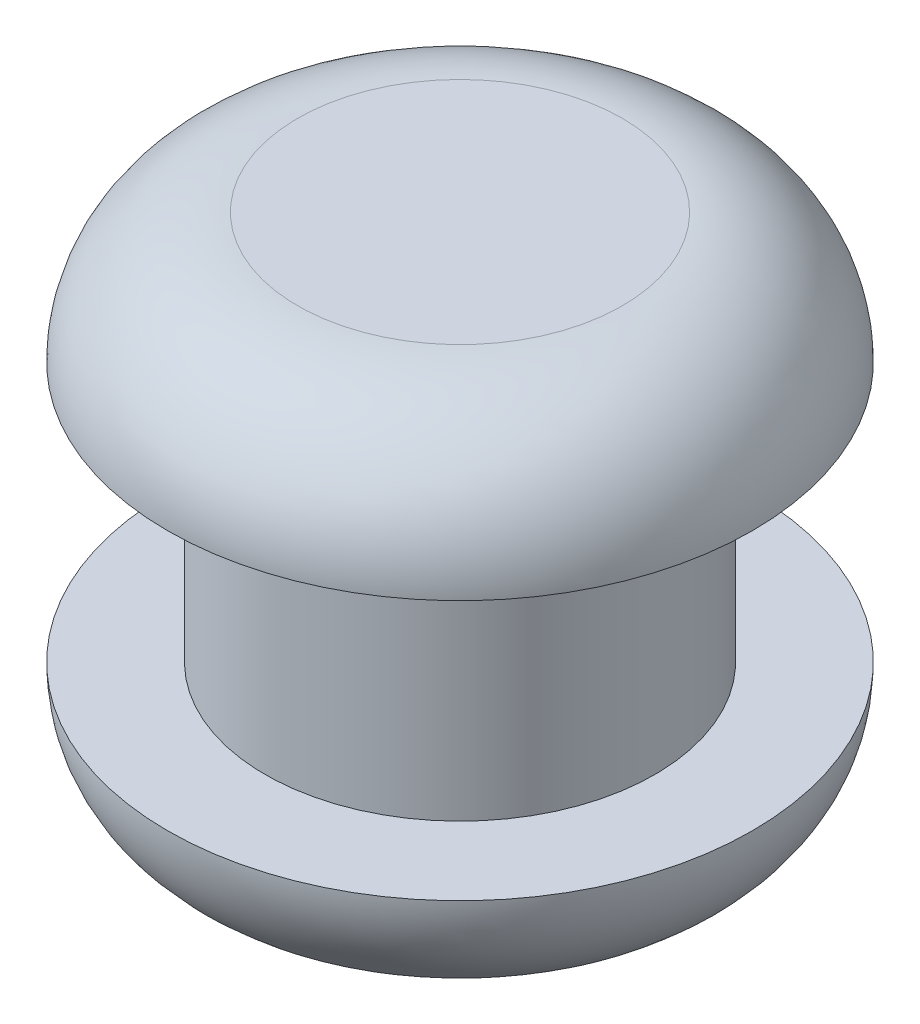
SolidWorks part; units mm, degrees
material "AISI 1045 Steel, cold drawn"
ref_plane "Front Plane" through (0, 0, 0) normal (1, 0, 0) x (0, 1, 0)
ref_plane "Top Plane" through (0, 0, 0) normal (0, 0, 1) x (0, 1, 0)
ref_plane "Right Plane" through (0, 0, 0) normal (0, 1, 0) x (-1, 0, 0)
sketch "Sketch2" plane through (0, 0, 0) normal (1, 0, 0) x (0, 1, 0)
  line L0 (-8.5466, 0) -> (8.2271, 0) construction
  line L1 (0, 5.8686) -> (0, -5.0584) construction
  line L2 (-2, 3) -> (2, 3)
  line L3 (2, 3) -> (2, 4.5)
  line L4 (2, 4.5) -> (4, 4.5) construction
  line L5 (4, 2.5) -> (4, 0)
  line L6 (4, 4.5) -> (4, 2.5) construction
  line L7 (-4, 2.5) -> (-4, 0)
  line L8 (-2, 3) -> (-2, 4.5)
  line L9 (-4, 0) -> (4, 0)
  arc A0 (2, 4.5) -> (4, 2.5) centre (2, 2.5) cw
  arc A1 (-2, 4.5) -> (-4, 2.5) centre (-2, 2.5) ccw
  point P17 (0, 3)
  dimension "D3" = 2
  dimension "D1" = 6
  dimension "D2" = 9
  dimension "D4" = 2
revolve "Revolve1" add sketch "Sketch2" angle 360 about L0
